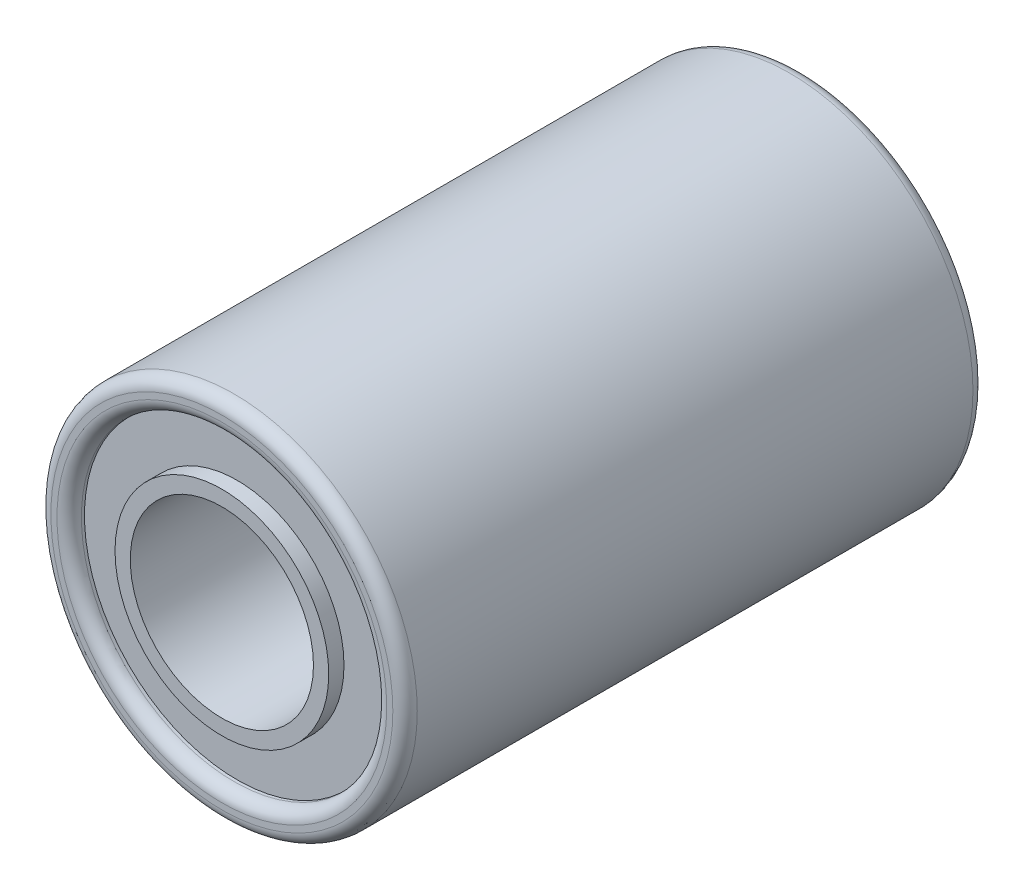
SolidWorks part; units mm, degrees
ref_plane "前视基准面" through (0, 0, 0) normal (0, 0, 1) x (1, 0, 0)
ref_plane "上视基准面" through (0, 0, 0) normal (0, 1, 0) x (1, 0, 0)
ref_plane "右视基准面" through (0, 0, 0) normal (1, 0, 0) x (0, 0, -1)
sketch "草图2" plane through (0, 0, 0) normal (0, 0, 1) x (1, 0, 0)
  circle A0 centre (0, 0) radius 6
  circle A1 centre (0, 0) radius 3
extrude "凸台-拉伸1" add sketch "草图2" along normal blind 19
sketch "草图3" plane through (0, 0, 19) normal (0, 0, 1) x (1, 0, 0)
  circle A0 centre (0, 0) radius 3.5
  circle A1 centre (0, 0) radius 5
extrude "切除-拉伸1" cut sketch "草图3" against normal blind 0.5
sketch "草图4" plane through (0, 0, 0) normal (0, 0, -1) x (-1, 0, 0)
  circle A0 centre (0, 0) radius 3.5
  circle A1 centre (0, 0) radius 5
extrude "切除-拉伸2" cut sketch "草图4" against normal blind 0.5
fillet "圆角1" radius 0.4 4 edges at (-5, 0, 0) (6, 0, 0) (5, 0, 19) (6, 0, 19)
